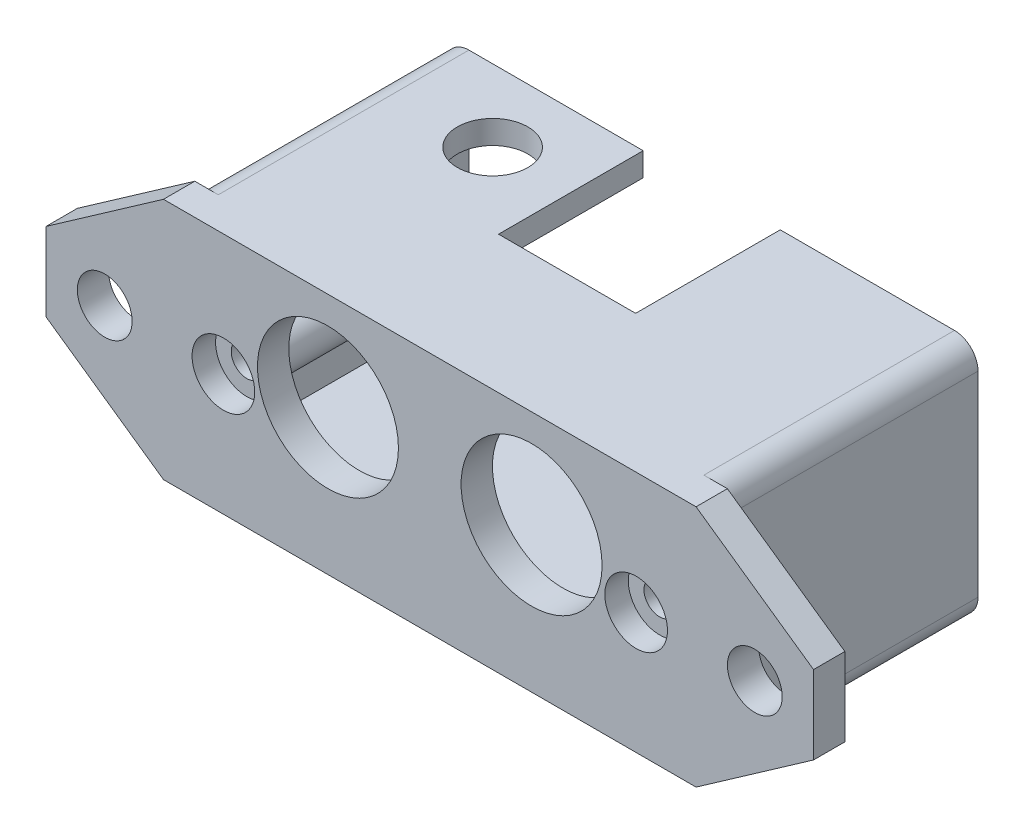
SolidWorks part; units mm, degrees
ref_plane "Alzado" through (0, 0, 0) normal (0, 0, 1) x (1, 0, 0)
ref_plane "Planta" through (0, 0, 0) normal (0, 1, 0) x (1, 0, 0)
ref_plane "Vista lateral" through (0, 0, 0) normal (1, 0, 0) x (0, 0, -1)
sketch "Croquis1" plane through (0, 0, 0) normal (0, 0, 1) x (1, 0, 0)
  line L0 (-34, 15.5) -> (34, 15.5)
  line L1 (49, -5) -> (34, -15.5)
  line L2 (-34, -15.5) -> (34, -15.5)
  line L3 (-49, 5) -> (-49, -5)
  line L4 (49, 5) -> (49, -5)
  line L6 (-49, 5) -> (-34, 15.5)
  line L8 (-49, -5) -> (-34, -15.5)
  line L13 (49, 5) -> (34, 15.5)
  circle A0 centre (-26.35, 0) radius 2
  circle A1 centre (26.35, 0) radius 2
  circle A4 centre (-41.5, 0) radius 3.5
  circle A5 centre (41.5, 0) radius 3.5
  circle A6 centre (-13, 3) radius 9
  circle A7 centre (13, 3) radius 9
extrude "Saliente-Extruir1" add sketch "Croquis1" along normal blind 4
sketch "Croquis3" plane through (0, 0, 0) normal (0, 0, 1) x (1, 0, 0)
  circle A0 centre (26.35, 0) radius 3
  circle A1 centre (-26.35, 0) radius 3
  circle A2 centre (26.35, 0) radius 2
  circle A3 centre (-26.35, 0) radius 2
extrude "Saliente-Extruir2" add sketch "Croquis3" against normal blind 12
sketch "Croquis4" plane through (0, 0, 0) normal (0, 0, 1) x (1, 0, 0)
  line L0 (31, 15.5) -> (-31, 15.5)
  line L1 (31, -15.5) -> (-31, -15.5)
  line L2 (34, 12.5) -> (34, -12.5)
  line L3 (-31, 12.5) -> (-31, -12.5)
  line L4 (-34, 12.5) -> (-34, -12.5)
  line L12 (31, 12.5) -> (31, -12.5)
  line L13 (31, -12.5) -> (-31, -12.5)
  line L14 (-31, 12.5) -> (31, 12.5)
  arc A0 (-34, 12.5) -> (-31, 15.5) centre (-31, 12.5) cw
  arc A1 (-34, -12.5) -> (-31, -15.5) centre (-31, -12.5) ccw
  arc A2 (31, -15.5) -> (34, -12.5) centre (31, -12.5) ccw
  arc A3 (34, 12.5) -> (31, 15.5) centre (31, 12.5) ccw
  point P7 (-34, 15.5)
  point P17 (-34, -15.5)
  point P20 (34, -15.5)
  point P23 (34, 15.5)
extrude "Saliente-Extruir3" add sketch "Croquis4" against normal blind 32
ref_plane "Plano1" through (0, 16, 0) normal (0, 1, 0) x (1, 0, 0)
sketch "Croquis5" plane through (0, 16, 0) normal (0, 1, 0) x (1, 0, 0)
  line L3 (-8.75, 13.5324) -> (8.75, 13.5324)
  line L4 (-8.75, 32.0149) -> (8.75, 32.0149)
  line L5 (-8.75, 32.0149) -> (-8.75, 13.5324)
  line L7 (8.75, 32.0149) -> (8.75, 13.5324)
  circle A0 centre (-18.75, 22.7737) radius 4.5
extrude "Cortar-Extruir1" cut sketch "Croquis5" against normal blind 18 and the other way blind 10
ref_plane "Plano2" through (0, 0, 4) normal (0, 0, 1) x (1, 0, 0)
sketch "Croquis6" plane through (0, 0, 4) normal (0, 0, 1) x (1, 0, 0)
  circle A0 centre (26.35, 0) radius 2
  circle A1 centre (26.35, 0) radius 4
  circle A2 centre (-26.35, 0) radius 2
  circle A3 centre (-26.35, 0) radius 4
extrude "Cortar-Extruir2" cut sketch "Croquis6" against normal blind 3
